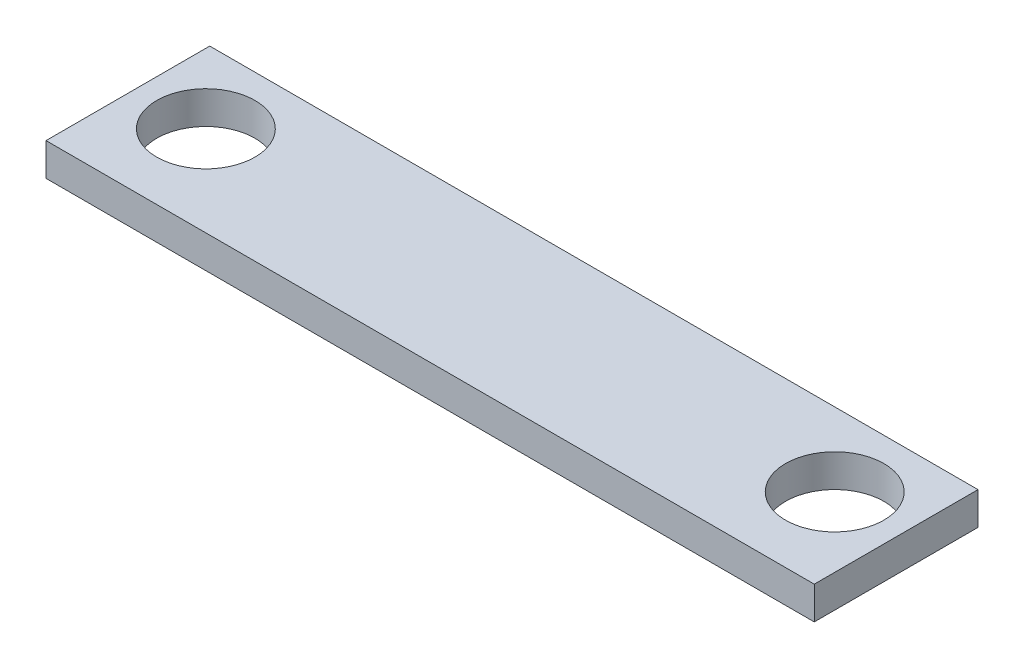
SolidWorks part; units mm, degrees
ref_plane "Front Plane" through (0, 0, 0) normal (0, 0, 1) x (1, 0, 0)
ref_plane "Top Plane" through (0, 0, 0) normal (0, 1, 0) x (1, 0, 0)
ref_plane "Right Plane" through (0, 0, 0) normal (1, 0, 0) x (0, 0, -1)
sketch "Sketch2" plane through (0, 0, 0) normal (0, 1, 0) x (1, 0, 0)
  line L1 (-11.73, 0) -> (11.73, 0)
  point P2 (0, 0)
extrude "Extrude-Thin1" add sketch "Sketch2" along normal blind 1 thin
sketch "Sketch3" plane through (0, 1, 0) normal (0, 1, 0) x (1, 0, 0)
  line L0 (0, -0.55) -> (0, 0.55) construction
  circle A0 centre (-9.6014, -2.2473) radius 1.5
  circle A1 centre (9.6014, -2.2473) radius 1.5
  point P2 (-52.1253, -2.0514)
  point P7 (-23.99, -1.9502)
  point P8 (-8.4963, -1.782)
  point P9 (-10.7506, -1.7597)
  point P10 (-8.9407, -1.6443)
  point P11 (-11.4136, -1.7573)
  point P12 (-9.6014, -2.2473)
extrude "Cut-Extrude1" cut sketch "Sketch3" against normal through all
